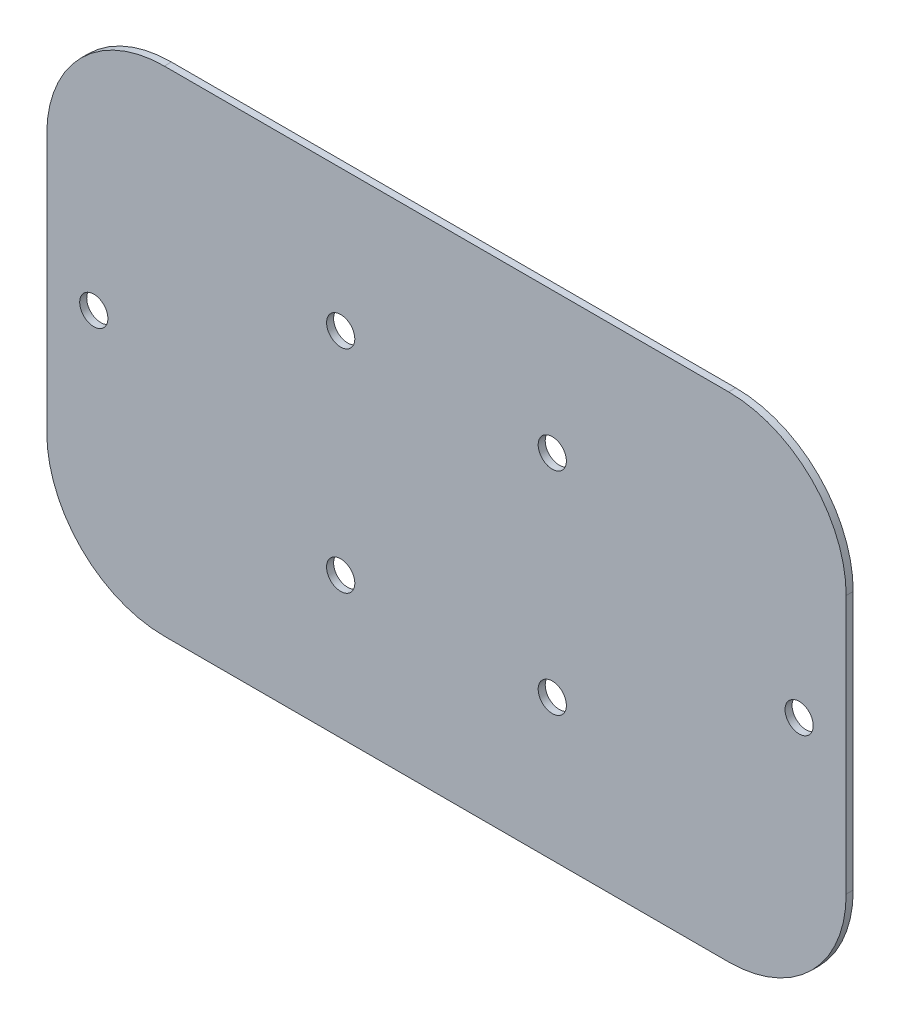
SolidWorks part; units mm, degrees
ref_plane "Płaszczyzna przednia" through (0, 0, 0) normal (0, 0, 1) x (1, 0, 0)
ref_plane "Płaszczyzna górna" through (0, 0, 0) normal (0, 1, 0) x (1, 0, 0)
ref_plane "Płaszczyzna prawa" through (0, 0, 0) normal (1, 0, 0) x (0, 0, -1)
sketch "Szkic1" plane through (0, 0, 0) normal (0, 0, 1) x (1, 0, 0)
  line L1 (-120, -105) -> (120, -105)
  line L2 (-170, -55) -> (-170, 55)
  line L3 (-120, 105) -> (120, 105)
  line L4 (170, -55) -> (170, 55)
  line L5 (-170, -105) -> (170, 105) construction
  line L6 (-170, 105) -> (170, -105) construction
  arc A0 (-120, -105) -> (-170, -55) centre (-120, -55) cw
  arc A1 (120, -105) -> (170, -55) centre (120, -55) ccw
  arc A2 (120, 105) -> (170, 55) centre (120, 55) cw
  arc A3 (-170, 55) -> (-120, 105) centre (-120, 55) cw
  point P0 (0, 0)
  dimension "D1" = 50
  dimension "D2" = 340
  dimension "D3" = 210
extrude "Dodanie-wyciągnięcie1" add sketch "Szkic1" along normal blind 3
hole_wizard "Otwory ustalające Ø12.0mm1" positions "Szkic2" profile "Szkic3" hole size "Ø12.0" standard "ISO" end condition through all
sketch "Szkic2" plane through (0, 0, 0) normal (0, 0, -1) x (-1, 0, 0)
  line L0 (0, 0) -> (0, -62.2789) construction
  line L2 (0, 0) -> (-132.7414, 0) construction
  point P0 (45, 45)
  point P2 (-45, 45)
  point P4 (45, -45)
  point P6 (-45, -45)
  point P10 (-150, 0)
  point P12 (150, 0)
  dimension "D1" = 45
  dimension "D2" = 45
  dimension "D3" = 0
  dimension "D5" = 150
  dimension "D6" = 150
  dimension "D7" = 45
  dimension "D8" = 45
sketch "Szkic3" plane through (-45, 45, 0) normal (1, 0, 0) x (0, 1, 0)
  line L0 (0, 0) -> (0, 3)
  line L1 (0, 3) -> (6, 3)
  line L2 (6, 3) -> (6, 0)
  line L5 (6, 0) -> (0, 0)
  line L11 (0, -6.35) -> (0, 107.95) construction
  dimension "Średnica otworu na wylot" = 12
  dimension "Głębokość otworu na wylot" = 3
